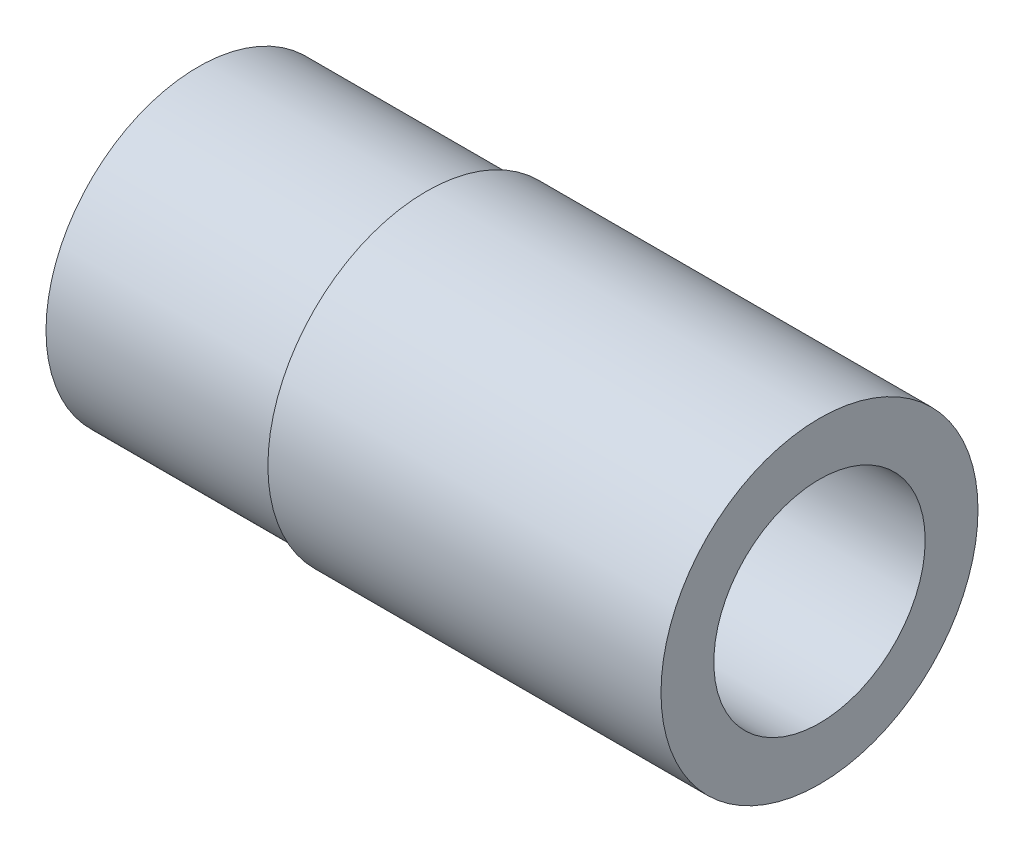
SolidWorks part; units mm, degrees
material "CK45"
ref_plane "Front Plane" through (0, 0, 0) normal (0, 0, 1) x (1, 0, 0)
ref_plane "Top Plane" through (0, 0, 0) normal (0, 1, 0) x (1, 0, 0)
ref_plane "Right Plane" through (0, 0, 0) normal (1, 0, 0) x (0, 0, -1)
sketch "Sketch1" plane through (0, 0, 0) normal (1, 0, 0) x (0, 0, -1)
  circle A0 centre (0, 0) radius 37.5
  dimension "D1" = 75
extrude "Boss-Extrude1" add sketch "Sketch1" along normal mid plane 147
sketch "Sketch2" plane through (73.5, 0, 0) normal (1, 0, 0) x (0, 0, -1)
  circle A0 centre (0, 0) radius 21
extrude "Cut-Extrude1" cut sketch "Sketch2" against normal through all
sketch "Sketch3" plane through (73.5, 0, 0) normal (1, 0, 0) x (0, 0, -1)
  circle A0 centre (0, 0) radius 25
extrude "Cut-Extrude2" cut sketch "Sketch3" against normal blind 36.5
sketch "Sketch4" plane through (-73.5, 0, 0) normal (-1, 0, 0) x (0, 0, 1)
  line L1 (-6, 3.3345) -> (6, 3.3345)
  line L2 (-6, 3.3345) -> (-6, 24.3)
  line L3 (-6, 24.3) -> (6, 24.3)
  line L4 (6, 3.3345) -> (6, 24.3)
  line L5 (-6, 3.3345) -> (6, 24.3) construction
  line L6 (-6, 24.3) -> (6, 3.3345) construction
  point P0 (0, 13.8172)
  dimension "D1" = 12
  dimension "D2" = 24.3
extrude "Cut-Extrude3" cut sketch "Sketch4" against normal up to surface (110.5 mm away) up to face at (37, 0, -25)
fillet "Fillet1" radius 0.5 1 edges at (37, -21, 0)
sketch "Sketch5" plane through (0, 0, 0) normal (0, 0, 1) x (1, 0, 0)
  line L0 (-73.5, 0) -> (82.8949, 0) construction
  line L1 (-73.5, 37.5) -> (-19.5, 37.5)
  line L2 (-73.5, 37.5) -> (-73.5, 36)
  line L3 (-73.5, 36) -> (-19.5, 36)
  line L4 (-19.5, 37.5) -> (-19.5, 36)
  line L5 (-73.5, 37.5) -> (-73.5, -37.5) construction
  dimension "D1" = 54
  dimension "D2" = 1.5
revolve "Cut-Revolve1" cut sketch "Sketch5" angle 360 about L0
